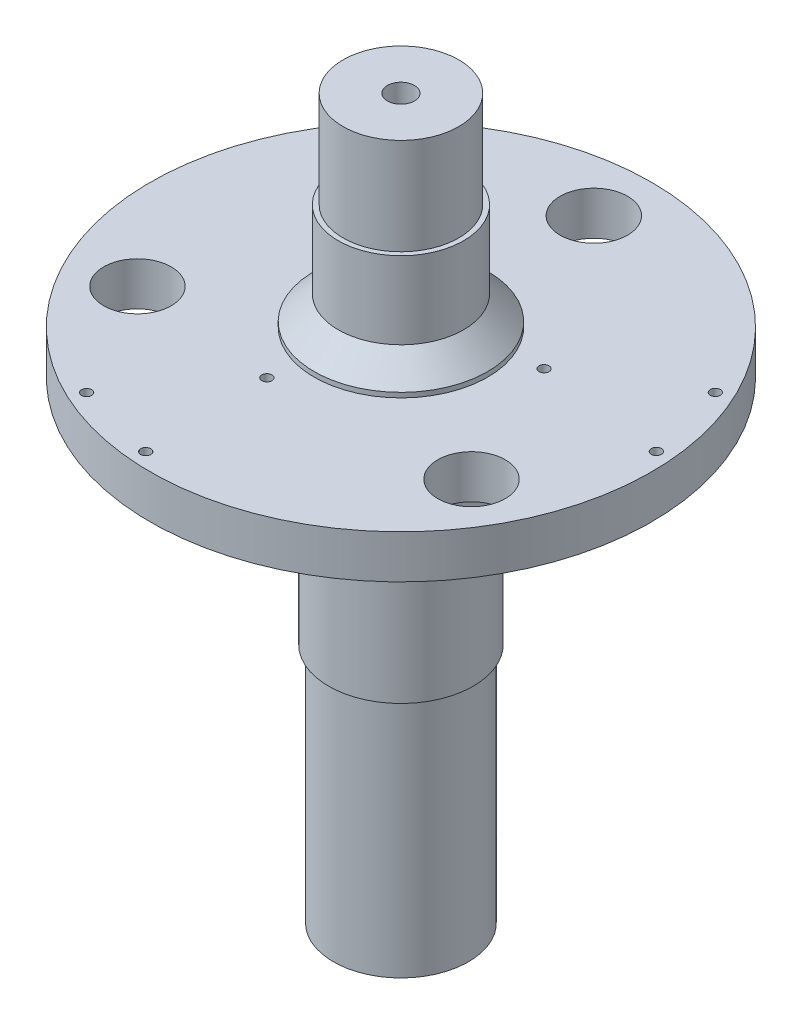
SolidWorks part; units mm, degrees
ref_plane "前视基准面" through (0, 0, 0) normal (0, 0, 1) x (1, 0, 0)
ref_plane "上视基准面" through (0, 0, 0) normal (0, 1, 0) x (1, 0, 0)
ref_plane "右视基准面" through (0, 0, 0) normal (1, 0, 0) x (0, 0, -1)
sketch "草图1" plane through (0, 0, 0) normal (0, 0, 1) x (1, 0, 0)
  line L0 (0, 0) -> (-60, 0)
  line L1 (-60, 0) -> (-60, -100)
  line L2 (-60, -100) -> (-65, -100)
  line L3 (-65, -100) -> (-65, -180)
  line L4 (-65, -180) -> (-90, -205)
  line L5 (-90, -205) -> (-90, -210)
  line L6 (-90, -210) -> (-260, -210)
  line L7 (-260, -210) -> (-260, -255)
  line L8 (-260, -255) -> (-75, -255)
  line L9 (-75, -255) -> (-75, -495)
  line L10 (-75, -495) -> (-70, -495)
  line L11 (-70, -495) -> (-70, -745)
  line L12 (-70, -745) -> (0, -745)
  line L13 (0, -745) -> (0, 0) construction
  line L14 (0, 0) -> (0, -745)
  point P14 (-65, -140)
  dimension "D1" = 120
  dimension "D2" = 130
  dimension "D3" = 180
  dimension "D4" = 520
  dimension "D5" = 150
  dimension "D6" = 140
  dimension "D7" = 100
  dimension "D8" = 210
  dimension "D9" = 45
  dimension "D10" = 240
  dimension "D11" = 250
  dimension "D12" = 5
  dimension "D13" = 45
revolve "旋转1" add sketch "草图1" angle 360 about L13
hole_wizard "M30x2.0 螺纹孔1" positions "草图2" profile "草图3" tap size "M30x2.0" standard "GB"
sketch "草图2" plane through (0, 0, 0) normal (0, 1, 0) x (1, 0, 0)
  point P0 (0, 0)
sketch "草图3" plane through (0, 0, 0) normal (1, 0, 0) x (0, 0, 1)
  line L0 (0, 0) -> (0, 68.412)
  line L1 (0, 68.412) -> (14, 60)
  line L2 (14, 60) -> (14, 0)
  line L5 (14, 0) -> (0, 0)
  line L10 (0, 68.412) -> (-14, 60) construction
  line L11 (0, -6.35) -> (0, 107.95) construction
  dimension "螺纹孔钻头直径" = 28
  dimension "螺纹孔钻头深度" = 60
  dimension "导头角度" = 118
cosmetic thread "孔螺蚊线1" parameters "D1"=50, "D2"=30
sketch "草图4" plane through (0, -210, 0) normal (0, 1, 0) x (1, 0, 0)
  line L0 (0, 0) -> (-173.2051, -100) construction
  line L1 (0, 0) -> (0, 275.1832) construction
  circle A0 centre (0, 0) radius 200 construction
  circle A1 centre (-173.2051, -100) radius 35
  dimension "D1" = 400
  dimension "D2" = 70
  dimension "D3" = 60
extrude "切除-拉伸1" cut sketch "草图4" against normal up to next
pattern_circular "阵列(圆周)1" count 3 over 360 about axis through (0, 0, 0) along (0, 1, 0) of "切除-拉伸1"
sketch "草图5" plane through (0, -210, 0) normal (0, 1, 0) x (1, 0, 0)
  line L0 (-23.9601, -115.0311) -> (-20.4644, -244.1438) construction
  line L1 (-20.4644, -244.1438) -> (-104.1065, -221.7811) construction
  line L2 (-104.1065, -221.7811) -> (-173.2051, -100) construction
  line L3 (-173.2051, -100) -> (-23.9601, -115.0311) construction
  line L4 (-104.1065, -221.7811) -> (-23.9601, -115.0311) construction
  line L5 (-173.2051, -100) -> (-20.4644, -244.1438) construction
  circle A0 centre (0, 0) radius 117.5 construction
  circle A1 centre (0, 0) radius 245 construction
  circle A2 centre (-23.9601, -115.0311) radius 5.25
  circle A3 centre (-104.1065, -221.7811) radius 5.25
  circle A4 centre (-20.4644, -244.1438) radius 5.25
  dimension "D1" = 235
  dimension "D2" = 490
  dimension "D3" = 150
  dimension "D6" = 10.5
  dimension "D4" = 129.16
  dimension "D5" = 86.58
extrude "切除-拉伸2" cut sketch "草图5" against normal blind 30
pattern_circular "阵列(圆周)2" count 3 over 360 about axis through (0, 0, 0) along (0, 1, 0) of "切除-拉伸2"
